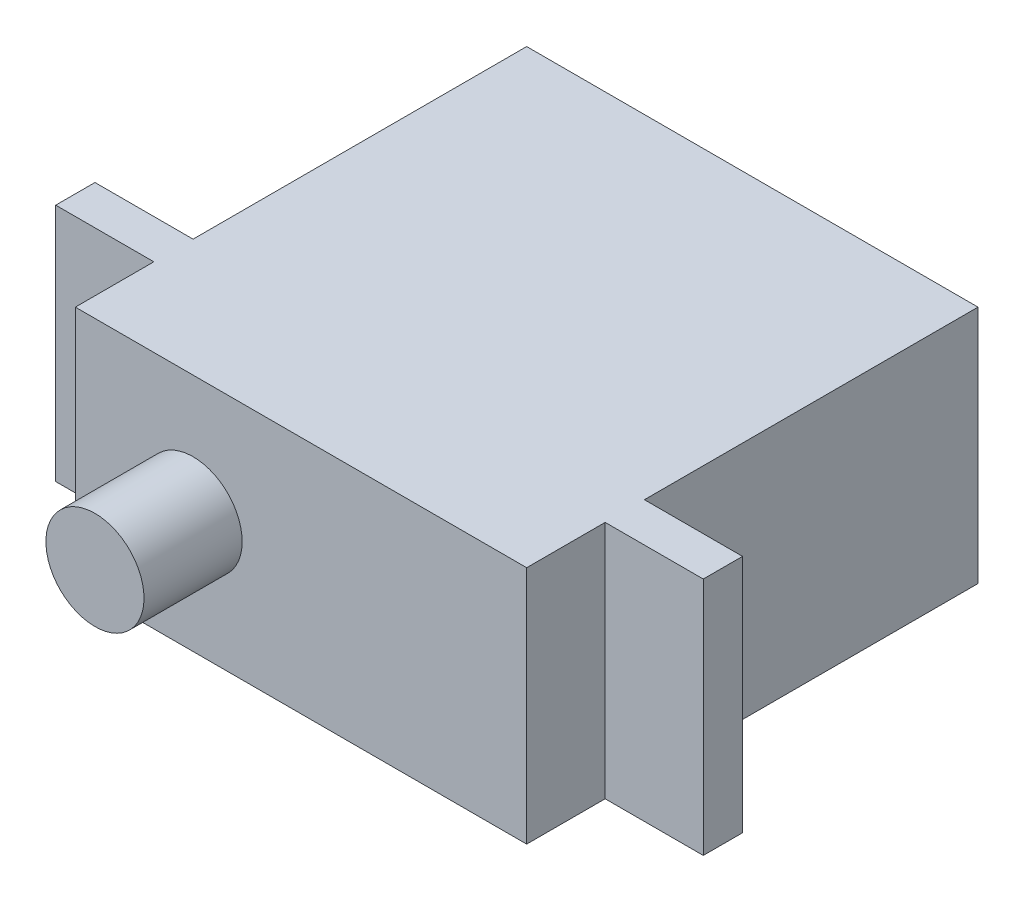
SolidWorks part; units mm, degrees
ref_plane "Front Plane" through (0, 0, 0) normal (0, 0, 1) x (1, 0, 0)
ref_plane "Top Plane" through (0, 0, 0) normal (0, 1, 0) x (1, 0, 0)
ref_plane "Right Plane" through (0, 0, 0) normal (1, 0, 0) x (0, 0, -1)
sketch "Case_23x12p2x23_profile" plane through (0, 0, 0) normal (0, 0, 1) x (1, 0, 0)
  line L1 (-6, -6.1) -> (17, -6.1)
  line L2 (-6, -6.1) -> (-6, 6.1)
  line L3 (-6, 6.1) -> (17, 6.1)
  line L4 (17, -6.1) -> (17, 6.1)
extrude "Case_23x12p2x23" add sketch "Case_23x12p2x23_profile" along normal blind 23 from offset 19
sketch "Mounting_ears_33x12p2_profile" plane through (0, 0, 0) normal (0, 0, 1) x (1, 0, 0)
  line L1 (-11, -6.1) -> (22, -6.1)
  line L2 (-11, -6.1) -> (-11, 6.1)
  line L3 (-11, 6.1) -> (22, 6.1)
  line L4 (22, -6.1) -> (22, 6.1)
extrude "Mounting_ears_33x12p2" add sketch "Mounting_ears_33x12p2_profile" along normal blind 2 from offset 2
sketch "Output_envelope_not_spline_profile" plane through (0, 0, 0) normal (0, 0, 1) x (1, 0, 0)
  circle A0 centre (0, 0) radius 2.5
extrude "Output_envelope_not_spline" add sketch "Output_envelope_not_spline_profile" along normal blind 5 from offset 4
sketch "Sketch4" plane through (0, 0, 0) normal (0, 0, 1) x (1, 0, 0)
  circle A0 centre (-9, 0) radius 1.1
  circle A1 centre (20, 0) radius 1.1
